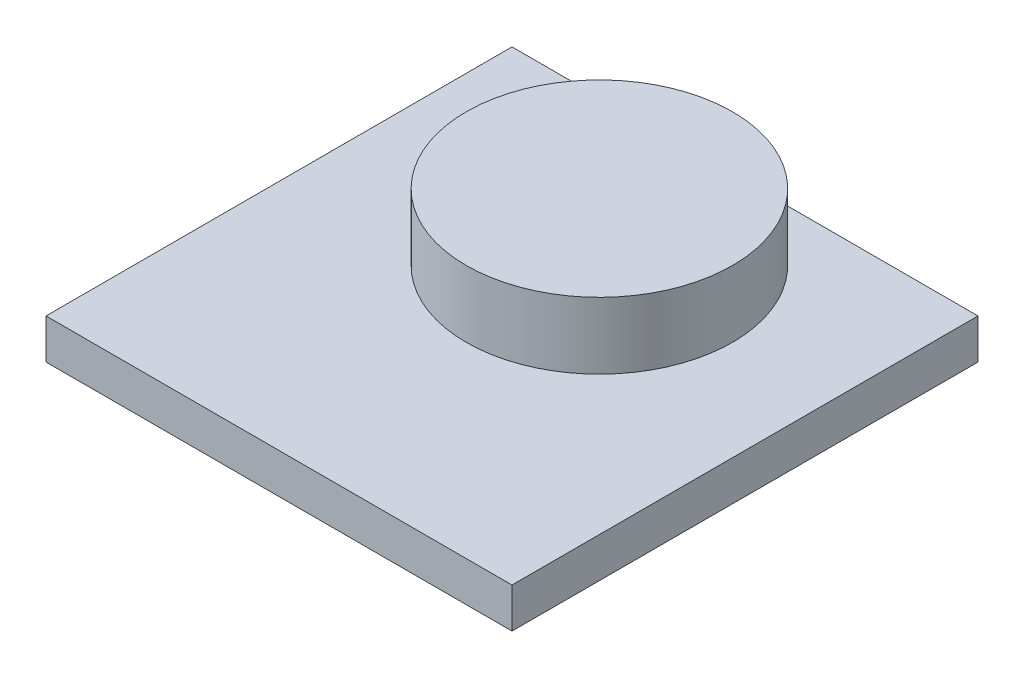
SolidWorks part; units mm, degrees
ref_plane "Front Plane" through (0, 0, 0) normal (0, 0, 1) x (1, 0, 0)
ref_plane "Top Plane" through (0, 0, 0) normal (0, 1, 0) x (1, 0, 0)
ref_plane "Right Plane" through (0, 0, 0) normal (1, 0, 0) x (0, 0, -1)
sketch "Sketch1" plane through (0, 0, 0) normal (0, 1, 0) x (1, 0, 0)
  line L0 (0, 0) -> (35, 0) construction
  line L1 (0, 0) -> (35, 0)
  line L2 (0, 0) -> (0, -35)
  line L3 (0, -35) -> (35, -35)
  line L4 (35, 0) -> (35, -35)
  line L5 (0, 0) -> (35, 0) construction
  line L6 (17.5, 0) -> (17.5, -35) construction
  line L7 (17.5, -35) -> (17.5, -17.5) construction
  line L8 (17.5, -17.5) -> (17.5, 0) construction
  line L9 (17.5, 0) -> (17.5, -8.75) construction
  line L10 (17.5, -8.75) -> (17.5, -17.5) construction
  line L11 (17.5, -17.5) -> (17.5, -13.125) construction
  line L12 (17.5, -8.75) -> (17.5, -10.9375) construction
  arc A1 (17.5, -13.125) -> (17.5, -8.75) centre (17.5, -10.9375) cw construction
  circle A2 centre (17.5, -10.9375) radius 10
  dimension "D1" = 35
  dimension "D2" = 35
extrude "Boss-Extrude1" add sketch "Sketch1" against normal blind 3 contours L2 L1 L4 L3
sketch "Sketch2" plane through (0, 0, 0) normal (0, 1, 0) x (1, 0, 0)
  line L0 (0, 0) -> (35, 0) construction
  line L1 (35, 0) -> (17.5, 0) construction
  line L2 (17.5, 0) -> (17.5, -35) construction
  line L3 (0, -35) -> (35, -35) construction
  line L4 (17.5, -35) -> (17.5, -17.5) construction
  line L5 (17.5, -17.5) -> (17.5, 0) construction
  line L6 (17.5, 0) -> (17.5, -8.75) construction
  line L7 (17.5, -8.75) -> (17.5, -17.5) construction
  line L8 (17.5, -17.5) -> (17.5, -13.125) construction
  line L9 (17.5, -13.125) -> (17.5, -8.75) construction
  line L10 (17.5, -8.75) -> (17.5, -10.9375) construction
  circle A0 centre (17.5, -10.9375) radius 10
extrude "Boss-Extrude2" add sketch "Sketch2" along normal blind 5
